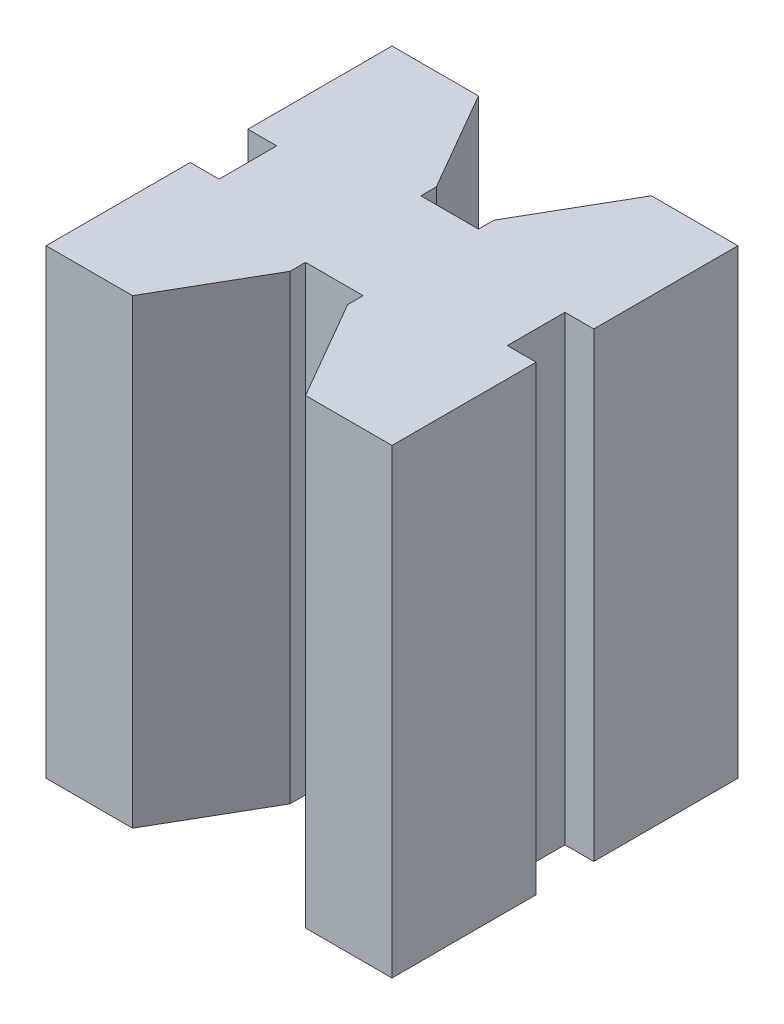
SolidWorks part; units mm, degrees
ref_plane "Front Plane" through (0, 0, 0) normal (0, 0, 1) x (1, 0, 0)
ref_plane "Top Plane" through (0, 0, 0) normal (0, 1, 0) x (1, 0, 0)
ref_plane "Right Plane" through (0, 0, 0) normal (1, 0, 0) x (0, 0, -1)
sketch "Sketch1" plane through (0, 0, 0) normal (0, 1, 0) x (1, 0, 0)
  line L68 (-30, -15) -> (0, -15) construction
  line L69 (-30, -12.5) -> (-27.5, -12.5)
  line L70 (-15, 0) -> (-15, -30) construction
  line L71 (-27.5, -12.5) -> (-27.5, -17.5)
  line L72 (-27.5, -17.5) -> (-30, -17.5)
  line L73 (0, -12.5) -> (-2.5, -12.5)
  line L74 (-2.5, -12.5) -> (-2.5, -17.5)
  line L75 (-2.5, -17.5) -> (0, -17.5)
  line L76 (-17.5, -20) -> (-17.5, -21.3397)
  line L77 (-7.5, -30) -> (-12.5, -21.3397)
  line L78 (-17.5, -20) -> (-12.5, -20)
  line L79 (-12.5, -20) -> (-12.5, -21.3397)
  line L80 (-17.5, -10) -> (-17.5, -8.6603)
  line L81 (-30, 0) -> (-30, -12.5)
  line L82 (-17.5, -10) -> (-12.5, -10)
  line L83 (-30, -17.5) -> (-30, -30)
  line L86 (-12.5, -10) -> (-12.5, -8.6603)
  line L88 (-30, 0) -> (-22.5, 0)
  line L89 (-7.5, 0) -> (0, 0)
  line L90 (-30, -30) -> (-22.5, -30)
  line L91 (-7.5, -30) -> (0, -30)
  line L92 (-17.5, -21.3397) -> (-22.5, -30)
  line L93 (-12.5, -8.6603) -> (-7.5, 0)
  line L94 (-22.5, 0) -> (-17.5, -8.6603)
  line L95 (0, -12.5) -> (0, 0)
  line L96 (0, -17.5) -> (0, -30)
  point P17 (-10, -25.6699)
  point P22 (-15, -20)
  point P26 (-15, -32.2661)
  point P32 (-14.7773, -23.9561)
  dimension "D1" = 30
  dimension "D2" = 5
  dimension "D3" = 10
  dimension "D4" = 5
  dimension "D5" = 15
  dimension "D6" = 25
  dimension "D7" = 30
  dimension "D8" = 60
  dimension "D9" = 60
  dimension "D10" = 60
  dimension "D11" = 60
  dimension "D12" = 1.3397
  dimension "D13" = 15
  dimension "D14" = 5
  dimension "D15" = 2.5
  dimension "D16" = 12.5
  dimension "D17" = 2.5
  dimension "D18" = 7.5
  dimension "D19" = 12.5
extrude "Boss-Extrude2" add sketch "Sketch1" along normal blind 40
